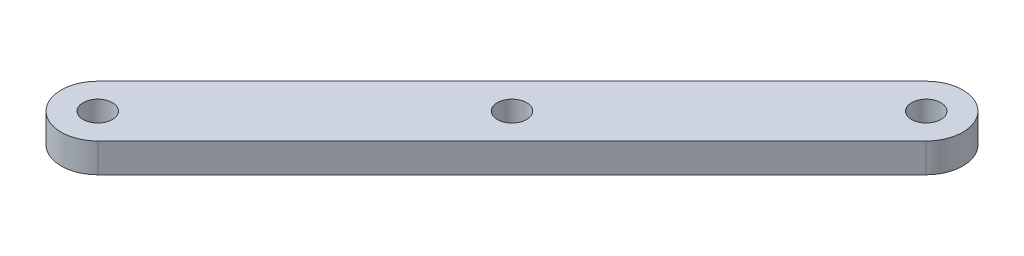
SolidWorks part; units mm, degrees
ref_plane "Ön Düzlem" through (0, 0, 0) normal (0, 0, 1) x (1, 0, 0)
ref_plane "Üst Düzlem" through (0, 0, 0) normal (0, 1, 0) x (1, 0, 0)
ref_plane "Sağ Düzlem" through (0, 0, 0) normal (1, 0, 0) x (0, 0, -1)
sketch "Sketch1" plane through (0, 0, 0) normal (0, 1, 0) x (1, 0, 0)
  line L1 (-8.8388, 8.8388) -> (132.5825, 150.2602)
  line L2 (150.2602, 132.5825) -> (8.8388, -8.8388)
  circle A0 centre (0, 0) radius 5
  arc A1 (-8.8388, 8.8388) -> (8.8388, -8.8388) centre (0, 0) ccw
  circle A2 centre (141.4214, 141.4214) radius 5
  arc A3 (150.2602, 132.5825) -> (132.5825, 150.2602) centre (141.4214, 141.4214) ccw
  circle A4 centre (70.7107, 70.7107) radius 5
  dimension "D1" = 10
  dimension "D2" = 12.5
  dimension "D3" = 10
  dimension "D4" = 12.5
  dimension "D6" = 100
  dimension "D5" = 200
extrude "Boss-Extrude1" add sketch "Sketch1" along normal blind 10
